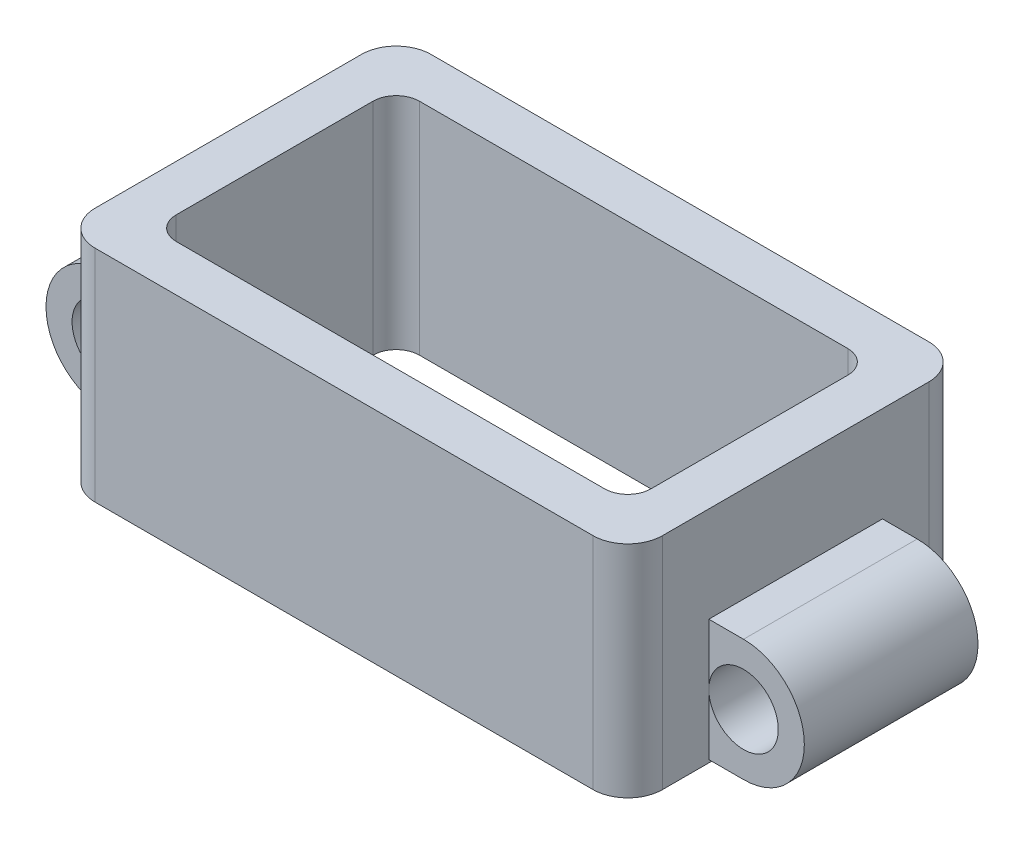
SolidWorks part; units mm, degrees
ref_plane "Plan de face" through (0, 0, 0) normal (0, 0, 1) x (1, 0, 0)
ref_plane "Plan de dessus" through (0, 0, 0) normal (0, 1, 0) x (1, 0, 0)
ref_plane "Plan de droite" through (0, 0, 0) normal (1, 0, 0) x (0, 0, -1)
sketch "Esquisse1" plane through (0, 0, 0) normal (0, 1, 0) x (1, 0, 0)
  line L1 (-57.0795, -4.1565) -> (-8.0795, -4.1565)
  line L2 (-57.0795, -4.1565) -> (-57.0795, -33.1565)
  line L3 (-57.0795, -33.1565) -> (-8.0795, -33.1565)
  line L4 (-8.0795, -4.1565) -> (-8.0795, -33.1565)
  line L5 (-53.0795, -8.1565) -> (-12.0795, -8.1565)
  line L6 (-53.0795, -8.1565) -> (-53.0795, -29.1565)
  line L7 (-53.0795, -29.1565) -> (-12.0795, -29.1565)
  line L8 (-12.0795, -8.1565) -> (-12.0795, -29.1565)
  dimension "D1" = 29
  dimension "D2" = 49
  dimension "D3" = 21
  dimension "D4" = 41
  dimension "D5" = 4
  dimension "D6" = 4
extrude "Boss.-Extru.1" add sketch "Esquisse1" along normal blind 19
fillet "Congé1" radius 3 4 edges at (-57.0795, 9.5, 4.1565) (-57.0795, 9.5, 33.1565) (-8.0795, 9.5, 4.1565) (-8.0795, 9.5, 33.1565)
fillet "Congé2" radius 2 4 edges at (-12.0795, 9.5, 8.1565) (-12.0795, 9.5, 29.1565) (-53.0795, 9.5, 29.1565) (-53.0795, 9.5, 8.1565)
sketch "Esquisse2" plane through (-8.0795, 0, 0) normal (1, 0, 0) x (0, 0, -1)
  line L0 (-33.1565, 0) -> (-33.1565, 19) construction
  line L1 (-26.1565, 0.25) -> (-11.1565, 0.25)
  line L2 (-26.1565, 0.25) -> (-26.1565, 10.75)
  line L3 (-26.1565, 10.75) -> (-11.1565, 10.75)
  line L4 (-11.1565, 0.25) -> (-11.1565, 10.75)
  line L6 (-30.1565, 0) -> (-7.1565, 0) construction
  point P4 (-24.7129, 2.3763)
  dimension "D1" = 10.5
  dimension "D2" = 15
  dimension "D3" = 0.25
  dimension "D4" = 7
extrude "Boss.-Extru.2" add sketch "Esquisse2" along normal blind 19
sketch "Esquisse3" plane through (-57.0795, 0, 0) normal (-1, 0, 0) x (0, 0, 1)
  line L0 (7.1565, 0) -> (30.1565, 0) construction
  line L1 (26.1565, 10.75) -> (11.1565, 10.75)
  line L2 (26.1565, 10.75) -> (26.1565, 0.25)
  line L3 (26.1565, 0.25) -> (11.1565, 0.25)
  line L4 (11.1565, 10.75) -> (11.1565, 0.25)
  dimension "D1" = 10.5
  dimension "D2" = 15
  dimension "D3" = 0.25
  dimension "D4" = 7
extrude "Boss.-Extru.3" add sketch "Esquisse3" along normal blind 19 contours L2 L3 L4 L1
sketch "Esquisse5" plane through (0, 0, 11.1565) normal (0, 0, -1) x (-1, 0, 0)
  line L0 (76.0795, 0.25) -> (57.0795, 0.25) construction
  line L2 (57.0795, 10.75) -> (57.0795, 0.25) construction
  circle A0 centre (60.0795, 5.5) radius 3
  dimension "D1" = 6
  dimension "D2" = 5.25
  dimension "D3" = 3
extrude "Enlèv. mat.-Extru.1" cut sketch "Esquisse5" against normal up to next contours A0
sketch "Esquisse7" plane through (0, 0, 11.1565) normal (0, 0, -1) x (-1, 0, 0)
  line L0 (76.0795, 0.25) -> (57.0795, 0.25) construction
  line L1 (76.0795, 10.75) -> (57.0795, 10.75) construction
  line L2 (60.0795, 0.25) -> (76.0795, 0.25)
  line L3 (76.0795, 0.25) -> (76.0795, 10.75)
  line L4 (76.0795, 10.75) -> (60.0795, 10.75)
  arc A0 (60.0795, 0.25) -> (60.0795, 10.75) centre (60.0795, 5.5) ccw
extrude "Enlèv. mat.-Extru.2" cut sketch "Esquisse7" against normal up to next
sketch "Esquisse8" plane through (0, 0, 11.1565) normal (0, 0, -1) x (-1, 0, 0)
  line L0 (-10.9205, 0.25) -> (8.0795, 0.25) construction
  line L1 (8.0795, 0.25) -> (8.0795, 10.75) construction
  circle A0 centre (5.0795, 5.5) radius 3
  dimension "D1" = 6
  dimension "D2" = 5.25
  dimension "D3" = 3
extrude "Enlèv. mat.-Extru.3" cut sketch "Esquisse8" against normal up to next
sketch "Esquisse9" plane through (0, 0, 11.1565) normal (0, 0, -1) x (-1, 0, 0)
  line L0 (-10.9205, 0.25) -> (8.0795, 0.25) construction
  line L1 (-10.9205, 10.75) -> (8.0795, 10.75) construction
  line L2 (5.0795, 0.25) -> (-10.9205, 0.25)
  line L3 (-10.9205, 0.25) -> (-10.9205, 10.75)
  line L4 (-10.9205, 10.75) -> (5.0795, 10.75)
  arc A0 (5.0795, 0.25) -> (5.0795, 10.75) centre (5.0795, 5.5) cw
extrude "Enlèv. mat.-Extru.4" cut sketch "Esquisse9" against normal up to next contours A0 L4 L3 L2
equation "\"D2@Esquisse5\"=(10.5)/2"
